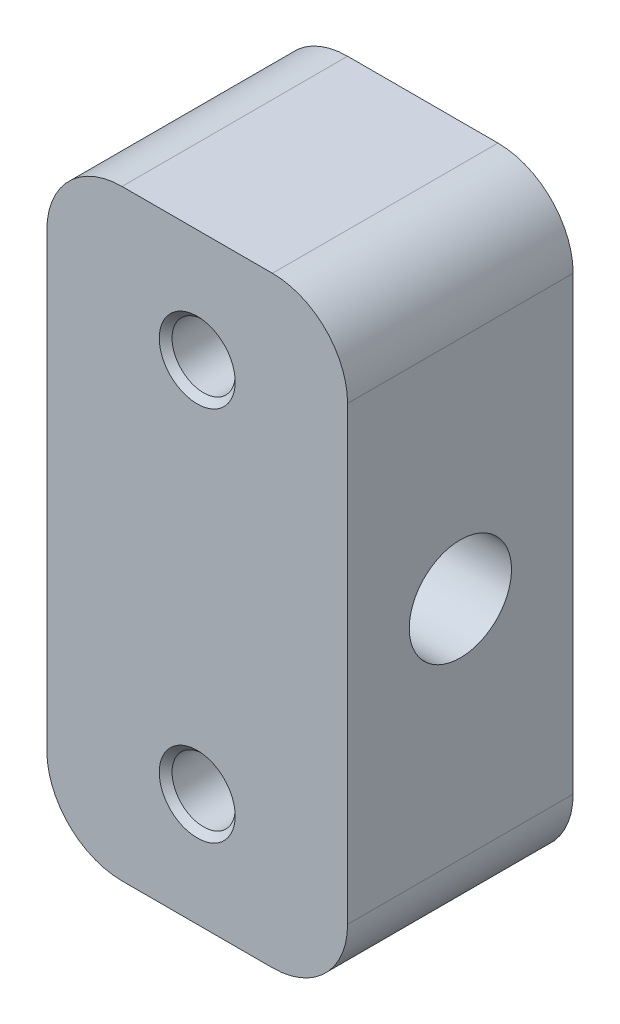
SolidWorks part; units mm, degrees
material "6063-T6"
ref_plane "Ön Düzlem" through (0, 0, 0) normal (0, 0, 1) x (1, 0, 0)
ref_plane "Üst Düzlem" through (0, 0, 0) normal (0, 1, 0) x (1, 0, 0)
ref_plane "Sağ Düzlem" through (0, 0, 0) normal (1, 0, 0) x (0, 0, -1)
sketch "Sketch1" plane through (0, 0, 0) normal (0, 0, 1) x (1, 0, 0)
  line L1 (-10, -20) -> (10, -20)
  line L2 (-10, -20) -> (-10, 20)
  line L3 (-10, 20) -> (10, 20)
  line L4 (10, -20) -> (10, 20)
  line L5 (-10, -20) -> (10, 20) construction
  line L6 (-10, 20) -> (10, -20) construction
  point P0 (0, 0)
  dimension "D1" = 20
  dimension "D2" = 40
extrude "Boss-Extrude1" add sketch "Sketch1" along normal mid plane 15
fillet "Fillet1" radius 5 4 edges at (-10, -20, 0) (10, -20, 0) (-10, 20, 0) (10, 20, 0)
sketch "Sketch2" plane through (0, 0, 7.5) normal (0, 0, 1) x (1, 0, 0)
  line L0 (0, -12.5) -> (0, 12.5) construction
  point P4 (0, 0)
  dimension "D1" = 25
hole_wizard "M5 Tapped Hole1" positions "Sketch3" profile "Sketch4" tap size "M5" standard "ISO" end condition through all
sketch "Sketch3" plane through (0, 0, 7.5) normal (0, 0, 1) x (1, 0, 0)
  point P0 (0, 12.5)
  point P3 (0, -12.5)
sketch "Sketch4" plane through (0, 12.5, 7.5) normal (1, 0, 0) x (0, -1, 0)
  line L0 (0, 0) -> (0, 15)
  line L1 (0, 15) -> (2.1, 15)
  line L2 (2.1, 15) -> (2.1, 0.425)
  line L3 (2.1, 0.425) -> (2.525, 0)
  line L5 (2.525, 0) -> (0, 0)
  line L6 (-2.1, 0.425) -> (-2.525, 0) construction
  line L11 (0, -6.35) -> (0, 107.95) construction
  dimension "Thru Tap Drill Dia." = 4.2
  dimension "Thru Tap Drill Depth" = 15
  dimension "Near C'Sink Dia." = 5.05
  dimension "Near C'Sink Angle" = 90
cosmetic thread "Hole Thread1" parameters "D2"=5
cosmetic thread "Hole Thread2" parameters "D2"=5
hole_wizard "M8 Tapped Hole1" positions "Sketch6" profile "Sketch7" tap size "M8" standard "ISO"
sketch "Sketch6" plane through (-10, 0, 0) normal (-1, 0, 0) x (0, 0, 1)
  point P0 (0, 0)
cosmetic thread "Hole Thread3" parameters "D1"=16, "D2"=8
sketch "Sketch7" plane through (-10, 0, 0) normal (0, 1, 0) x (0, 0, 1)
  line L0 (0, 0) -> (0, 22.0429)
  line L1 (0, 22.0429) -> (3.4, 20)
  line L2 (3.4, 20) -> (3.4, 0.625)
  line L3 (3.4, 0.625) -> (4.025, 0)
  line L5 (4.025, 0) -> (0, 0)
  line L6 (-3.4, 0.625) -> (-4.025, 0) construction
  line L10 (0, 22.0429) -> (-3.4, 20) construction
  line L11 (0, -6.35) -> (0, 107.95) construction
  dimension "Tap Drill Dia." = 6.8
  dimension "Tap Drill Depth" = 20
  dimension "Near C'Sink Dia." = 8.05
  dimension "Near C'Sink Angle" = 90
  dimension "Drill Angle" = 118
